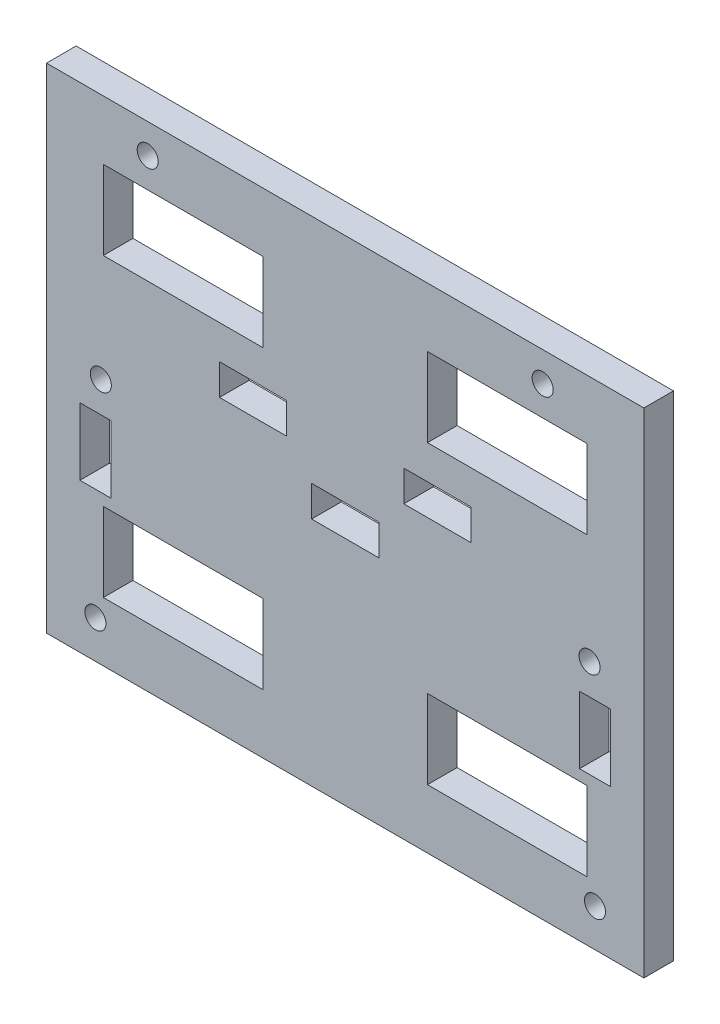
SolidWorks part; units mm, degrees
ref_plane "Front Plane" through (0, 0, 0) normal (0, 0, 1) x (1, 0, 0)
ref_plane "Top Plane" through (0, 0, 0) normal (0, 1, 0) x (1, 0, 0)
ref_plane "Right Plane" through (0, 0, 0) normal (1, 0, 0) x (0, 0, -1)
sketch "Sketch1" plane through (0, 0, 0) normal (0, 0, 1) x (1, 0, 0)
  line L0 (0, -37.5) -> (0, 37.5) construction
  line L1 (-45.375, -37.5) -> (45.375, -37.5)
  line L2 (-45.375, -37.5) -> (-45.375, 37.5)
  line L3 (-45.375, 37.5) -> (45.375, 37.5)
  line L4 (45.375, -37.5) -> (45.375, 37.5)
  line L5 (-45.375, -37.5) -> (45.375, 37.5) construction
  line L6 (-45.375, 37.5) -> (45.375, -37.5) construction
  line L7 (-45.375, 0) -> (45.375, 0) construction
  line L8 (-45.375, 22.5) -> (45.375, 22.5) construction
  line L9 (36.75, 16.5) -> (12.5, 28.5) construction
  line L10 (-36.75, 28.5) -> (-12.5, 28.5)
  line L11 (-36.75, 28.5) -> (-36.75, 16.5)
  line L12 (-36.75, 16.5) -> (-12.5, 16.5)
  line L13 (-12.5, 28.5) -> (-12.5, 16.5)
  line L14 (-36.75, 28.5) -> (-12.5, 16.5) construction
  line L15 (-36.75, 16.5) -> (-12.5, 28.5) construction
  line L16 (36.75, 28.5) -> (12.5, 16.5) construction
  line L17 (12.5, 28.5) -> (12.5, 16.5)
  line L18 (36.75, 16.5) -> (12.5, 16.5)
  line L19 (36.75, 28.5) -> (36.75, 16.5)
  line L20 (36.75, 28.5) -> (12.5, 28.5)
  line L21 (36.75, -28.5) -> (12.5, -16.5) construction
  line L22 (-36.75, -16.5) -> (-12.5, -28.5) construction
  line L23 (-36.75, -28.5) -> (-12.5, -16.5) construction
  line L24 (36.75, -16.5) -> (12.5, -28.5) construction
  line L25 (36.75, -28.5) -> (12.5, -28.5)
  line L26 (36.75, -28.5) -> (36.75, -16.5)
  line L27 (36.75, -16.5) -> (12.5, -16.5)
  line L28 (12.5, -28.5) -> (12.5, -16.5)
  line L29 (-12.5, -28.5) -> (-12.5, -16.5)
  line L30 (-36.75, -16.5) -> (-12.5, -16.5)
  line L31 (-36.75, -28.5) -> (-36.75, -16.5)
  line L32 (-36.75, -28.5) -> (-12.5, -28.5)
  point P0 (0, 0)
  point P12 (-24.625, 22.5)
  point P21 (24.625, 22.5)
  point P30 (24.625, -22.5)
  point P31 (-24.625, -22.5)
  dimension "D1" = 90.75
  dimension "D2" = 75
  dimension "D3" = 22.5
  dimension "D4" = 24.25
  dimension "D5" = 12
  dimension "D6" = 12.5
extrude "Boss-Extrude1" add sketch "Sketch1" along normal blind 4.5
sketch "Sketch2" plane through (0, 0, 4.5) normal (0, 0, 1) x (1, 0, 0)
  line L0 (0, -37.5) -> (0, 37.5) construction
  line L1 (-45.375, -37.5) -> (45.375, -37.5) construction
  line L2 (45.375, 37.5) -> (-45.375, 37.5) construction
  line L3 (-45.375, 0) -> (45.375, 0) construction
  line L4 (-45.375, 37.5) -> (-45.375, -37.5) construction
  line L5 (45.375, -37.5) -> (45.375, 37.5) construction
  line L6 (-37.125, 0) -> (37.125, 0) construction
  circle A0 centre (-30, 33) radius 1.6
  circle A1 centre (30, 33) radius 1.6
  circle A2 centre (37.125, 0) radius 1.6
  circle A3 centre (-37.125, 0) radius 1.6
  dimension "D1" = 3.2
  dimension "D7" = 3.2
  dimension "D8" = 3.2
  dimension "D2" = 30
  dimension "D3" = 33
  dimension "D4" = 74.25
  dimension "D5" = 37.125
  dimension "D6" = 0
extrude "screwHoles" cut sketch "Sketch2" against normal through all
sketch "Sketch3" plane through (0, 0, 4.5) normal (0, 0, 1) x (1, 0, 0)
  line L0 (-45.375, 9) -> (26.0486, 9) construction
  line L1 (-45.375, 37.5) -> (-45.375, -37.5) construction
  line L3 (0, 37.5) -> (0, -37.5) construction
  line L4 (45.375, 37.5) -> (-45.375, 37.5) construction
  line L5 (-45.375, -37.5) -> (45.375, -37.5) construction
  line L6 (19.1, 6.65) -> (8.9, 11.35) construction
  line L7 (-19.1, 11.35) -> (-8.9, 11.35)
  line L8 (-19.1, 11.35) -> (-19.1, 6.65)
  line L9 (-19.1, 6.65) -> (-8.9, 6.65)
  line L10 (-8.9, 11.35) -> (-8.9, 6.65)
  line L11 (-19.1, 11.35) -> (-8.9, 6.65) construction
  line L12 (-19.1, 6.65) -> (-8.9, 11.35) construction
  line L13 (19.1, 11.35) -> (8.9, 6.65) construction
  line L14 (8.9, 11.35) -> (8.9, 6.65)
  line L15 (19.1, 6.65) -> (8.9, 6.65)
  line L16 (19.1, 11.35) -> (19.1, 6.65)
  line L17 (19.1, 11.35) -> (8.9, 11.35)
  line L18 (-45.375, 37.5) -> (-45.375, -37.5) construction
  point P2 (-45.375, 0)
  point P12 (-14, 9)
  point P21 (14, 9)
  dimension "D1" = 10.2
  dimension "D2" = 4.7
  dimension "D3" = 14
  dimension "D4" = 9
extrude "BeltClamp" cut sketch "Sketch3" against normal through all
sketch "Sketch4" plane through (0, 0, 4.5) normal (0, 0, 1) x (1, 0, 0)
  line L0 (-45.375, 0) -> (45.375, 0) construction
  line L1 (-45.375, 37.5) -> (-45.375, -37.5) construction
  line L2 (45.375, -37.5) -> (45.375, 37.5) construction
  line L4 (-5.1, 2.35) -> (5.1, 2.35)
  line L5 (-5.1, 2.35) -> (-5.1, -2.35)
  line L6 (-5.1, -2.35) -> (5.1, -2.35)
  line L7 (5.1, 2.35) -> (5.1, -2.35)
  line L8 (-5.1, 2.35) -> (5.1, -2.35) construction
  line L9 (-5.1, -2.35) -> (5.1, 2.35) construction
  circle A0 centre (-37.125, 0) radius 1.6 construction
  point P6 (0, 0)
  dimension "D1" = 10.2
  dimension "D2" = 4.7
  dimension "D3" = 0
extrude "Cut-Extrude3" cut sketch "Sketch4" against normal through all
sketch "Sketch5" plane through (0, 0, 4.5) normal (0, 0, 1) x (1, 0, 0)
  line L0 (-45.375, -9.75) -> (45.375, -9.75) construction
  line L1 (-45.375, 37.5) -> (-45.375, -37.5) construction
  line L2 (45.375, -37.5) -> (45.375, 37.5) construction
  line L3 (5.1, -2.35) -> (5.1, 2.35) construction
  line L4 (0, -37.5) -> (0, 37.5) construction
  line L5 (-45.375, -37.5) -> (45.375, -37.5) construction
  line L6 (45.375, 37.5) -> (-45.375, 37.5) construction
  line L7 (-35.6, -14.85) -> (-40.3, -4.65) construction
  line L8 (35.6, -4.65) -> (40.3, -4.65)
  line L9 (35.6, -4.65) -> (35.6, -14.85)
  line L10 (35.6, -14.85) -> (40.3, -14.85)
  line L11 (40.3, -4.65) -> (40.3, -14.85)
  line L12 (35.6, -4.65) -> (40.3, -14.85) construction
  line L13 (35.6, -14.85) -> (40.3, -4.65) construction
  line L14 (-35.6, -4.65) -> (-40.3, -14.85) construction
  line L15 (-40.3, -4.65) -> (-40.3, -14.85)
  line L16 (-35.6, -14.85) -> (-40.3, -14.85)
  line L17 (-35.6, -4.65) -> (-35.6, -14.85)
  line L18 (-35.6, -4.65) -> (-40.3, -4.65)
  line L19 (37.95, -9.75) -> (37.95, -37.5) construction
  line L20 (-37.95, -9.75) -> (-37.95, -37.5) construction
  circle A0 centre (37.95, -31.75) radius 1.6
  circle A1 centre (-37.95, -31.75) radius 1.6
  point P6 (5.1, 0)
  point P15 (37.95, -9.75)
  point P24 (-37.95, -9.75)
  dimension "D5" = 3.2
  dimension "D1" = 9.75
  dimension "D2" = 10.2
  dimension "D3" = 4.7
  dimension "D4" = 37.95
  dimension "D6" = 22
extrude "Cut-Extrude4" cut sketch "Sketch5" against normal through all
sketch "Sketch6" plane through (0, 0, 4.5) normal (0, 0, 1) x (1, 0, 0)
  line L0 (-40.3, -9.75) -> (40.3, -9.75) construction
  line L1 (-40.3, -4.65) -> (-40.3, -14.85) construction
  line L2 (40.3, -14.85) -> (40.3, -4.65) construction
  line L3 (0, -2.35) -> (0, -37.5) construction
  line L4 (-5.1, -2.35) -> (5.1, -2.35) construction
  line L5 (-45.375, -37.5) -> (45.375, -37.5) construction
  line L6 (37.95, -14.85) -> (37.95, -4.65) construction
  line L7 (35.6, -14.85) -> (40.3, -14.85) construction
  line L8 (40.3, -4.65) -> (35.6, -4.65) construction
  line L9 (35.6, -4.65) -> (35.6, -14.85) construction
  line L10 (34.6, -15.85) -> (41.3, -15.85)
  line L11 (34.6, -15.85) -> (34.6, -3.65)
  line L12 (34.6, -3.65) -> (41.3, -3.65)
  line L13 (41.3, -15.85) -> (41.3, -3.65)
  line L14 (34.6, -15.85) -> (41.3, -3.65) construction
  line L15 (34.6, -3.65) -> (41.3, -15.85) construction
  line L16 (-34.6, -3.65) -> (-41.3, -15.85) construction
  line L17 (-34.6, -15.85) -> (-41.3, -3.65) construction
  line L18 (-37.95, -14.85) -> (-37.95, -4.65) construction
  line L19 (-41.3, -15.85) -> (-41.3, -3.65)
  line L20 (-34.6, -3.65) -> (-41.3, -3.65)
  line L21 (-34.6, -15.85) -> (-34.6, -3.65)
  line L22 (-34.6, -15.85) -> (-41.3, -15.85)
  circle A0 centre (37.95, -9.75) radius 1.6
  circle A1 centre (-37.95, -9.75) radius 1.6
  point P18 (37.95, -9.75)
  dimension "D3" = 3.2
  dimension "D1" = 1
  dimension "D2" = 1
extrude "FrontToRear1" [suppressed] add sketch "Sketch6" against normal up to surface (4.5 mm away)
sketch "Sketch7" plane through (0, 0, 4.5) normal (0, 0, 1) x (1, 0, 0)
  line L0 (5.1, 2.35) -> (-5.1, 2.35) construction
  line L1 (-42.125, -3.35) -> (42.125, -3.35)
  line L2 (-42.125, -3.35) -> (-42.125, 3.35)
  line L3 (-42.125, 3.35) -> (42.125, 3.35)
  line L4 (42.125, -3.35) -> (42.125, 3.35)
  line L5 (-42.125, -3.35) -> (42.125, 3.35) construction
  line L6 (-42.125, 3.35) -> (42.125, -3.35) construction
  circle A0 centre (37.125, 0) radius 1.6 construction
  point P0 (0, 0)
  dimension "D1" = 1
  dimension "D2" = 5
extrude "FrontToRear2" [suppressed] add sketch "Sketch7" against normal through all
equation "\"X-ROD-SPACING\"=45"
equation "\"Y-ROD-SPACING\"=75"
equation "\"Z-ROD-SPACING\"=17.5"
equation "\"Y-BED-OFFSET\"=2"
equation "\"Y-BED-ROD-INSET\"=3.5"
equation "\"Y-BED-SCREW-SPACING\"=209"
equation "\"Y-BED-SCREW-CUTOUT-SLOT-HEIGHT\"=1"
equation "\"T-SLOT-NUT-FILLET-RADIUS\"=0.25"
equation "\"T-SLOT-SCREW-SHAFT-RADIUS\"=1.75"
equation "\"T-SLOT-SCREW-SHAFT-CUTOUT-LENGTH\"=10.5"
equation "\"T-SLOT-NUT-DEPTH\"=4.2"
equation "\"T-SLOT-NUT-WIDTH\"=3"
equation "\"T-SLOT-NUT-END-DISTANCE\"=8"
equation "\"ACRYLIC-THICKNESS\"=10"
equation "\"ACRYLIC-THICKNESS2\"=4.5"
equation "\"ACRYLIC-TAB-CUTOUT-SIZE\"=\"ACRYLIC-THICKNESS\"+\"ACRYLIC-TAB-TOLERANCE\"*2"
equation "\"ACRYLIC-TAB-WIDTH\"=\"ACRYLIC-THICKNESS\""
equation "\"ACRYLIC-M3-HOLE\"=3.2"
equation "\"SMOOTHROD-CAP-SCREW-DISTANCE\"=20"
equation "\"FRAME-WIDTH-INNER\"=370"
equation "\"NEMA17-HOLE-SPACING\"=31"
equation "\"NEMA17-CENTRAL-CUTOUT\"=22.5"
equation "\"Z-BRACKET-REACH\"=55"
equation "\"Z-ROD-INSET\"=16"
equation "\"TOP-BRACKET-SPACING\"=40"
equation "\"SMOOTHROD-X-LENGTH\"=350"
equation "\"SMOOTHROD-Y-LENGTH\"=350"
equation "\"SMOOTHROD-Z-LENGTH\"=350"
equation "\"SMOOTHROD-TIGHTENING-HEADROOM\"=1"
equation "\"LEADSCREW-Z-LENGTH\"=300"
equation "\"SCREW-LENGTH-FRAME\"=\"ACRYLIC-THICKNESS\" + 10"
equation "\"SCREW-LENGTH-MOTOR\"=\"ACRYLIC-THICKNESS\" + 5"
equation "\"SCREW-HEAD-RADIUS\"=6"
equation "\"PRINTED-X-SMOOTHROD-DIAMETER\"=8.2"
equation "\"PRINTED-X-SMOOTHROD-CUTOUT\"=10"
equation "\"PRINTED-X-BASE-HEIGHT\"=10"
equation "\"PRINTED-LM8UU-CUTOUT-SIZE\"=16"
equation "\"PRINTED-LM8UU-CUTOUT-LENGTH\"=24.5"
equation "\"PRINTED-X-IDLER-HEIGHT\"=16"
equation "\"PSU-MOUNTING-WIDTH\"=95"
equation "\"PSU-MOUNTING-HEIGHT\"=177"
equation "\"Y-BELT-TO-ROD-DISTANCE\"=20"
equation "\"SPOOL-HOLDER-ROD-SPACING\"=150"
equation "\"D3@Sketch1\"=\"X-ROD-SPACING\"/2"
equation "\"D4@Sketch1\"=\"ACRYLIC-X-CARRIAGE-LM8UU-CUTOUT-WIDTH\""
equation "\"D1@Boss-Extrude1\"=\"ACRYLIC-THICKNESS2\""
equation "\"D1@Sketch2\"=\"ACRYLIC-M3-HOLE\""
equation "\"D1@Sketch3\"=\"ACRYLIC-TAB-CUTOUT-SIZE\""
equation "\"D2@Sketch3\"=\"ACRYLIC-THICKNESS2\"+\"ACRYLIC-TAB-TOLERANCE\"*2"
equation "\"ACRYLIC-X-CARRIAGE-WIDTH\"=55"
equation "\"ACRYLIC-X-CARRIAGE-HEIGHT\"=75"
equation "\"D1@Sketch1\"=\"ACRYLIC-X-CARRIAGE-WIDTH\"*\"ACRYLIC-X-CARRIAGE-DUAL-WIDTH-MULTIPLIER\""
equation "\"D2@Sketch1\"=\"ACRYLIC-X-CARRIAGE-HEIGHT\""
equation "\"ACRYLIC-X-CARRIAGE-CENTER-TAB-SPACING\"=14"
equation "\"D3@Sketch3\"=\"ACRYLIC-X-CARRIAGE-CENTER-TAB-SPACING\""
equation "\"SCREW-LENGTH-EXTRUDER\"=28"
equation "\"ACRYLIC-X-CARRIAGE-SCREW-SPACING-X\"=15"
equation "\"ACRYLIC-X-CARRIAGE-SCREW-SPACING-Y\"=33"
equation "\"D2@Sketch2\"=\"ACRYLIC-X-CARRIAGE-SCREW-SPACING-X\"*2"
equation "\"D3@Sketch2\"=\"ACRYLIC-X-CARRIAGE-SCREW-SPACING-Y\""
equation "\"D1@Sketch4\"=\"ACRYLIC-TAB-CUTOUT-SIZE\""
equation "\"D2@Sketch4\"=\"ACRYLIC-THICKNESS2\"+\"ACRYLIC-TAB-TOLERANCE\"*2"
equation "\"D2@Sketch5\"=\"ACRYLIC-TAB-CUTOUT-SIZE\""
equation "\"D3@Sketch5\"=\"ACRYLIC-THICKNESS2\"+\"ACRYLIC-TAB-TOLERANCE\"*2"
equation "\"ACRYLIC-X-CARRIAGE-EXTRUDER-SHELF-DEPTH\"=\"ACRYLIC-X-CARRIAGE-EXTRUDER-OFFSET\" + 30"
equation "\"ACRYLIC-X-CARRIAGE-EXTRUDER-BRACE-SPACING\"=23"
equation "\"D4@Sketch5\"=\"ACRYLIC-X-CARRIAGE-EXTRUDER-BRACE-SPACING\"*\"ACRYLIC-X-CARRIAGE-DUAL-WIDTH-MULTIPLIER\""
equation "\"D1@Sketch5\"=\"ACRYLIC-THICKNESS2\"/2 + 7.5"
equation "\"D4@Sketch2\"=\"ACRYLIC-X-CARRIAGE-SCREW-SPACING-X\"*\"ACRYLIC-X-CARRIAGE-DUAL-WIDTH-MULTIPLIER\"*1.5*2"
equation "\"D5@Sketch2\"=\"ACRYLIC-X-CARRIAGE-SCREW-SPACING-X\"*\"ACRYLIC-X-CARRIAGE-DUAL-WIDTH-MULTIPLIER\"*1.5"
equation "\"D7@Sketch2\"=\"ACRYLIC-M3-HOLE\""
equation "\"D8@Sketch2\"=\"ACRYLIC-M3-HOLE\""
equation "\"ACRYLIC-X-CARRIAGE-LM8UU-CUTOUT-WIDTH\"=24.25"
equation "\"ACRYLIC-TAB-TOLERANCE\"=.1"
equation "\"ACRYLIC-X-CARRIAGE-EXTRUDER-OFFSET\"=26"
equation "\"ACRYLIC-X-CARRIAGE-EXTRUDER-ANGLE\"=90"
equation "\"ACRYLIC-X-CARRIAGE-EXTRUDER-BRACE-TAB-OFFSET\"=20"
equation "\"ACRYLIC-X-CARRIAGE-EXTRUDER-BRACE-HEIGHT\"=35"
equation "\"ACRYLIC-X-CARRIAGE-EXTRUDER-BRACE-SCREW-SPACING\"=22"
equation "\"D5@Sketch5\"=\"ACRYLIC-M3-HOLE\""
equation "\"D3@Sketch6\"=\"ACRYLIC-M3-HOLE\""
equation "\"ACRYLIC-X-CARRIAGE-DUAL-WIDTH-MULTIPLIER\"=1.65"
